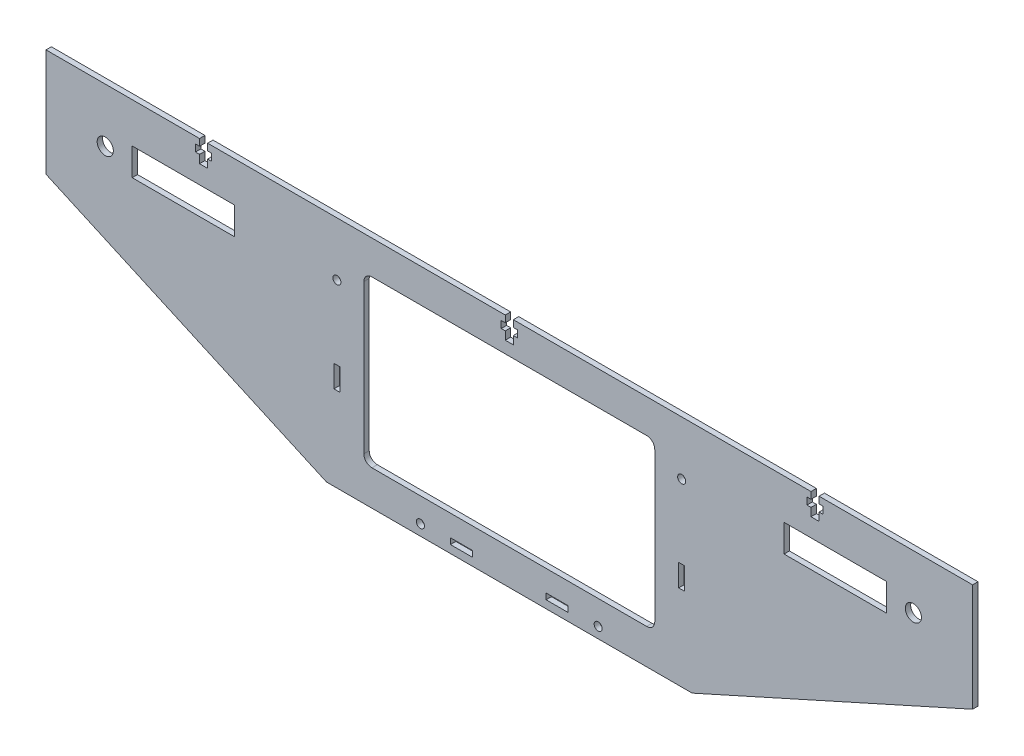
SolidWorks part; units mm, degrees
ref_plane "前视基准面" through (0, 0, 0) normal (0, 0, 1) x (1, 0, 0)
ref_plane "上视基准面" through (0, 0, 0) normal (0, 1, 0) x (1, 0, 0)
ref_plane "右视基准面" through (0, 0, 0) normal (1, 0, 0) x (0, 0, -1)
sketch "草图1" plane through (0, 0, 0) normal (0, 0, 1) x (1, 0, 0)
  line L0 (21.5651, -10.096) -> (13.5651, -8.096) construction
  line L1 (32.8151, -9.096) -> (-33.1849, -9.096) construction
  line L3 (-34.6849, -10.096) -> (-31.6849, -8.096) construction
  line L4 (-21.9349, -10.096) -> (-13.9349, -8.096) construction
  line L5 (-22.0349, -10.196) -> (-13.8349, -10.196)
  line L6 (-13.8349, -7.996) -> (-13.8349, -10.196)
  line L7 (-22.0349, -7.996) -> (-13.8349, -7.996)
  line L8 (-22.0349, -7.996) -> (-22.0349, -10.196)
  line L12 (-52.1849, -13.096) -> (-18.9349, -13.096)
  line L13 (64.9151, 18.2415) -> (62.7151, 18.2415)
  line L15 (34.3151, -10.096) -> (31.3151, -8.096) construction
  line L16 (21.6651, -7.996) -> (21.6651, -10.196)
  line L17 (21.6651, -7.996) -> (13.4651, -7.996)
  line L18 (13.4651, -7.996) -> (13.4651, -10.196)
  line L19 (67.6951, -13.096) -> (18.5651, -13.096)
  line L20 (64.9151, 18.2415) -> (64.9151, 26.4415)
  line L21 (-18.9349, -13.096) -> (18.5651, -13.096)
  line L22 (64.9151, 26.4415) -> (62.7151, 26.4415)
  line L25 (-63.0849, 18.2415) -> (-63.0849, 26.4415)
  line L26 (-65.2849, 26.4415) -> (-63.0849, 26.4415)
  line L27 (-65.2849, 18.2415) -> (-65.2849, 26.4415)
  line L28 (-65.2849, 18.2415) -> (-63.0849, 18.2415)
  line L29 (21.6651, -10.196) -> (13.4651, -10.196)
  line L34 (62.7151, 18.2415) -> (62.7151, 26.4415)
  line L35 (-52.1849, -13.096) -> (-68.0618, -13.096)
  line L41 (-49.1849, 53.779) -> (-49.1849, 33.779) construction
  line L42 (-49.1849, 53.779) -> (-49.1849, 73.779) construction
  line L46 (-172.1849, 73.779) -> (-172.1849, 33.779)
  line L47 (54.8151, 73.779) -> (54.8151, 87.1175) construction
  line L48 (54.8151, 87.1175) -> (171.8151, 87.1175) construction
  line L49 (-49.1849, 33.779) -> (206.8345, 33.779) construction
  line L50 (113.3151, 87.1175) -> (113.3151, 11.0003) construction
  line L51 (54.8151, 87.1175) -> (-62.1849, 87.1175) construction
  line L52 (-0.1849, -9.096) -> (-0.1849, 138.1567) construction
  line L53 (-1.6849, 71.279) -> (-3.1849, 71.279)
  line L59 (67.6951, -13.096) -> (171.8151, 33.779)
  line L60 (171.8151, 73.779) -> (171.8151, 33.779)
  line L61 (1.3151, 71.279) -> (2.8151, 71.279)
  line L62 (1.3151, 73.779) -> (1.3151, 71.279)
  line L63 (-3.1849, 71.279) -> (-3.1849, 68.679)
  line L64 (-3.1849, 68.679) -> (-1.6849, 68.679)
  line L65 (-1.6849, 68.679) -> (-1.6849, 65.679)
  line L66 (1.3151, 65.679) -> (-1.6849, 65.679)
  line L67 (1.3151, 68.679) -> (1.3151, 65.679)
  line L68 (2.8151, 68.679) -> (1.3151, 68.679)
  line L69 (2.8151, 71.279) -> (2.8151, 68.679)
  line L70 (-1.6849, 71.279) -> (-1.6849, 73.779)
  line L71 (-68.0618, 73.779) -> (-1.6849, 73.779)
  line L73 (-0.1849, 73.779) -> (-0.1849, 71.279) construction
  line L74 (139.8151, 53.779) -> (149.8151, 53.779) construction
  line L76 (114.8151, 73.779) -> (171.8151, 73.779)
  line L77 (111.8151, 71.279) -> (110.3151, 71.279)
  line L78 (114.8151, 71.279) -> (116.3151, 71.279)
  line L79 (114.8151, 73.779) -> (114.8151, 71.279)
  line L80 (110.3151, 71.279) -> (110.3151, 68.679)
  line L81 (110.3151, 68.679) -> (111.8151, 68.679)
  line L82 (111.8151, 68.679) -> (111.8151, 65.679)
  line L83 (114.8151, 65.679) -> (111.8151, 65.679)
  line L84 (114.8151, 68.679) -> (114.8151, 65.679)
  line L85 (116.3151, 68.679) -> (114.8151, 68.679)
  line L86 (116.3151, 71.279) -> (116.3151, 68.679)
  line L87 (111.8151, 71.279) -> (111.8151, 73.779)
  line L88 (114.8151, 65.679) -> (124.8151, 65.679) construction
  line L89 (113.3151, 73.779) -> (113.3151, 71.279) construction
  line L91 (1.3151, 73.779) -> (111.8151, 73.779)
  line L92 (124.8151, 53.779) -> (124.8151, 48.679) construction
  line L97 (124.8151, 48.679) -> (139.8151, 48.679)
  line L98 (139.8151, 48.679) -> (139.8151, 58.879)
  line L99 (139.8151, 58.879) -> (124.8151, 58.879)
  line L100 (111.8151, 65.679) -> (101.8151, 65.679) construction
  line L101 (101.8151, 58.879) -> (101.8151, 48.679)
  line L102 (101.8151, 48.679) -> (124.8151, 48.679)
  line L103 (124.8151, 58.879) -> (101.8151, 58.879)
  line L104 (-0.1849, 22.3415) -> (67.6951, 22.3415) construction
  line L105 (53.8151, 58.279) -> (53.8151, 2.904)
  line L106 (63.8151, 71.279) -> (-64.1849, 71.279) construction
  line L107 (63.8151, 71.279) -> (63.8151, -10.096) construction
  line L108 (63.8151, -10.096) -> (-64.1849, -10.096) construction
  line L109 (-64.1849, 71.279) -> (-64.1849, -10.096) construction
  line L110 (50.8151, -0.096) -> (-51.1849, -0.096)
  line L111 (-54.1849, 58.279) -> (-54.1849, 2.904)
  line L112 (50.8151, 61.279) -> (-51.1849, 61.279)
  line L113 (53.8151, -0.096) -> (-54.1849, -0.096) construction
  line L114 (53.8151, 61.279) -> (53.8151, -0.096) construction
  line L115 (-54.1849, 61.279) -> (-54.1849, -0.096) construction
  line L116 (53.8151, 61.279) -> (-54.1849, 61.279) construction
  line L117 (101.8151, 53.779) -> (63.8151, 53.779) construction
  line L118 (-102.1849, 53.779) -> (-64.1849, 53.779) construction
  line L119 (-112.1849, 65.679) -> (-102.1849, 65.679) construction
  line L120 (-125.1849, 53.779) -> (-125.1849, 48.679) construction
  line L121 (-113.6849, 73.779) -> (-113.6849, 71.279) construction
  line L122 (-115.1849, 65.679) -> (-125.1849, 65.679) construction
  line L123 (-140.1849, 53.779) -> (-150.1849, 53.779) construction
  line L124 (-113.6849, 87.1175) -> (-113.6849, 11.0003) construction
  line L125 (-125.1849, 58.879) -> (-102.1849, 58.879)
  line L126 (-102.1849, 48.679) -> (-125.1849, 48.679)
  line L127 (-102.1849, 58.879) -> (-102.1849, 48.679)
  line L128 (-140.1849, 58.879) -> (-125.1849, 58.879)
  line L129 (-140.1849, 48.679) -> (-140.1849, 58.879)
  line L130 (-125.1849, 48.679) -> (-140.1849, 48.679)
  line L131 (-112.1849, 73.779) -> (-68.0618, 73.779)
  line L132 (-112.1849, 71.279) -> (-112.1849, 73.779)
  line L133 (-116.6849, 71.279) -> (-116.6849, 68.679)
  line L134 (-116.6849, 68.679) -> (-115.1849, 68.679)
  line L135 (-115.1849, 68.679) -> (-115.1849, 65.679)
  line L136 (-115.1849, 65.679) -> (-112.1849, 65.679)
  line L137 (-112.1849, 68.679) -> (-112.1849, 65.679)
  line L138 (-110.6849, 68.679) -> (-112.1849, 68.679)
  line L139 (-110.6849, 71.279) -> (-110.6849, 68.679)
  line L140 (-115.1849, 73.779) -> (-115.1849, 71.279)
  line L141 (-115.1849, 71.279) -> (-116.6849, 71.279)
  line L142 (-112.1849, 71.279) -> (-110.6849, 71.279)
  line L143 (-115.1849, 73.779) -> (-172.1849, 73.779)
  line L144 (-68.0618, -13.096) -> (-172.1849, 33.779)
  circle A0 centre (-33.1849, -9.096) radius 1.5
  circle A2 centre (32.8151, -9.096) radius 1.5
  circle A11 centre (149.8151, 53.779) radius 3
  arc A12 (50.8151, -0.096) -> (53.8151, 2.904) centre (50.8151, 2.904) ccw
  arc A13 (-51.1849, -0.096) -> (-54.1849, 2.904) centre (-51.1849, 2.904) cw
  arc A14 (-54.1849, 58.279) -> (-51.1849, 61.279) centre (-51.1849, 58.279) cw
  arc A15 (50.8151, 61.279) -> (53.8151, 58.279) centre (50.8151, 58.279) cw
  circle A16 centre (-64.1849, 53.779) radius 1.5
  circle A17 centre (63.8151, 53.779) radius 1.5
  circle A18 centre (-150.1849, 53.779) radius 3
  point P66 (-19.749, 73.5671)
  dimension "D1" = 10
  dimension "D2" = 3
  dimension "D4" = 3
extrude "凸台-拉伸1" add sketch "草图1" along normal blind 2 contours L12 L21 L19
sketch "草图3" plane through (0, 73.779, 0) normal (0, 1, 0) x (1, 0, 0)
  line L0 (-1.6849, -1) -> (1.3151, -1)
  line L1 (-1.6849, -2) -> (-1.6849, 0) construction
  line L2 (1.3151, -2) -> (1.3151, 0) construction
  line L3 (111.8151, -1) -> (114.8151, -1)
  line L4 (111.8151, -2) -> (111.8151, 0) construction
  line L5 (114.8151, -2) -> (114.8151, 0) construction
  circle A0 centre (-0.1849, -1) radius 1.5
  circle A1 centre (113.3151, -1) radius 1.5
